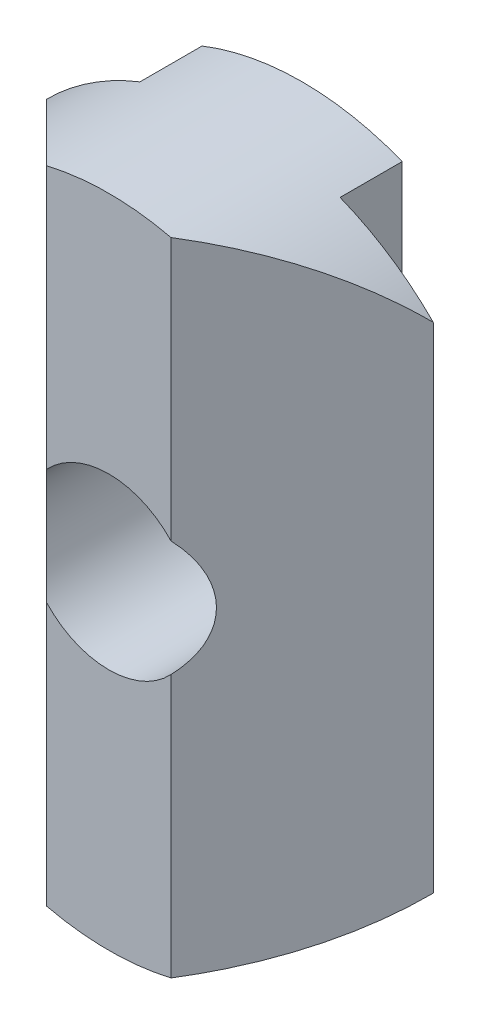
SolidWorks part; units mm, degrees
ref_plane "Plan de face" through (0, 0, 0) normal (0, 0, 1) x (1, 0, 0)
ref_plane "Plan de dessus" through (0, 0, 0) normal (0, 1, 0) x (1, 0, 0)
ref_plane "Plan de droite" through (0, 0, 0) normal (1, 0, 0) x (0, 0, -1)
sketch "Esquisse2" plane through (0, 0, 0) normal (0, 1, 0) x (1, 0, 0)
  line L0 (0, 0) -> (0, 2.8) construction
  line L1 (0.9, 0) -> (2.8, 1.9)
  line L2 (2.8, 1.9) -> (1.45, 1.9)
  line L3 (1.45, 1.9) -> (1.45, 2.8)
  line L4 (1.45, 2.8) -> (-1.45, 2.8)
  line L5 (0.9, 0) -> (-0.9, 0)
  line L6 (0, 1.9) -> (2.8, 1.9) construction
  line L7 (-0.9, 0) -> (-2.8, 1.9)
  line L8 (-2.8, 1.9) -> (-1.45, 1.9)
  line L9 (-1.45, 1.9) -> (-1.45, 2.8)
  dimension "D1" = 2.9
  dimension "D2" = 5.6
  dimension "D3" = 1.9
  dimension "D4" = 1.8
  dimension "D5" = 0.9
extrude "Boss.-Extru.1" add sketch "Esquisse2" along normal mid plane 9.5
sketch "Esquisse1" plane through (0, 0, 0) normal (0, 0, 1) x (1, 0, 0)
  line L0 (-5.1135, 0) -> (4.5072, 0) construction
  line L1 (-2.8, -3.5817) -> (-2.8, 3.5817)
  line L2 (2.8, 3.5817) -> (2.8, -3.5817)
  line L3 (0, 0) -> (0, 5.431) construction
  line L4 (0.9, 4.75) -> (0.9, -4.75) construction
  line L5 (1.45, 4.75) -> (1.45, -4.75) construction
  line L6 (-0.9, 4.75) -> (-0.9, -4.75) construction
  line L7 (0.9, 4.75) -> (2.8, 4.75) construction
  line L8 (-1.45, 4.75) -> (-1.45, -4.75) construction
  arc A0 (-2.8, 3.5817) -> (2.8, 3.5817) centre (0, 0.8105) cw
  arc A1 (-2.8, -3.5817) -> (2.8, -3.5817) centre (0, -0.8105) ccw
  point P3 (0, -4.75)
  point P8 (-2.8, 0)
  point P13 (2.8, 0)
  point P14 (0, 4.75)
  point P15 (1.45, 4.4734)
  point P17 (0.9, 4.6458)
  point P25 (-0.9, 4.6458)
  point P27 (-1.45, 4.4734)
  point P29 (1.45, 4.4734)
  point P30 (2.8, 3.5817)
  point P31 (-2.8, 3.5817)
  point P32 (-0.9, 4.6458)
  dimension "D1" = 5.6
  dimension "D2" = 1.8
extrude "Enlèv. mat.-Extru.1" cut sketch "Esquisse1" against normal through all flip side to cut
hole_wizard "Trou taraudé M31" positions "Esquisse3" profile "Esquisse4" tap size "M3" standard "ISO" end condition through all
sketch "Esquisse3" plane through (0, 0, -2.8) normal (0, 0, -1) x (-1, 0, 0)
  point P0 (0, 0)
sketch "Esquisse4" plane through (0, 0, -2.8) normal (1, 0, 0) x (0, 1, 0)
  line L0 (0, 0) -> (0, 2.8)
  line L1 (0, 2.8) -> (1.2294, 2.8)
  line L2 (1.2294, 2.8) -> (1.2294, 0)
  line L5 (1.2294, 0) -> (0, 0)
  line L11 (0, -6.35) -> (0, 107.95) construction
  dimension "Diamètre du trou pour taraudage jusqu'au prochain" = 2.4588
  dimension "Profondeur du trou pour taraudage jusqu'au prochain" = 2.8
cosmetic thread "Filetage de perçage1" parameters "D2"=3
equation "\"Diamètre du trou pour taraudage jusqu'au prochain@Esquisse4\"=2.45875"
